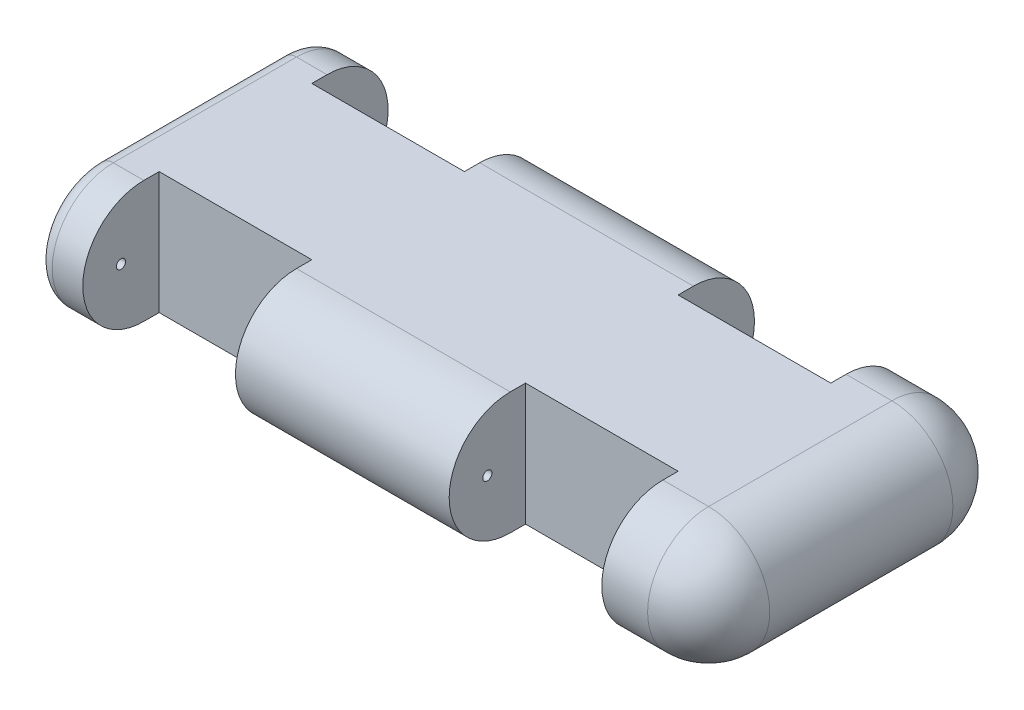
SolidWorks part; units mm, degrees
ref_plane "Front Plane" through (0, 0, 0) normal (0, 0, 1) x (1, 0, 0)
ref_plane "Top Plane" through (0, 0, 0) normal (0, 1, 0) x (1, 0, 0)
ref_plane "Right Plane" through (0, 0, 0) normal (1, 0, 0) x (0, 0, -1)
sketch "Sketch1" plane through (0, 0, 0) normal (0, 1, 0) x (1, 0, 0)
  line L0 (-70, -50) -> (70, -50) construction
  line L1 (-200, 100) -> (-170, 100)
  line L2 (-200, 100) -> (-200, -100)
  line L3 (-200, -100) -> (-170, -100)
  line L4 (200, 100) -> (200, -100)
  line L6 (-170, 100) -> (-170, 50)
  line L7 (-170, 50) -> (-70, 50)
  line L8 (-70, 100) -> (-70, 50)
  line L10 (70, 100) -> (70, 50)
  line L11 (70, 50) -> (170, 50)
  line L12 (170, 100) -> (170, 50)
  line L14 (-170, -100) -> (-170, -50)
  line L15 (-170, -50) -> (-70, -50)
  line L16 (-70, -100) -> (-70, -50)
  line L18 (70, -100) -> (70, -50)
  line L19 (70, -50) -> (170, -50)
  line L20 (170, -100) -> (170, -50)
  line L21 (-70, 50) -> (70, 50) construction
  line L22 (-170, -50) -> (-170, 50) construction
  line L23 (-70, 100) -> (70, 100)
  line L24 (170, 100) -> (200, 100)
  line L25 (170, -100) -> (200, -100)
  line L26 (-70, -100) -> (70, -100)
  point P20 (0, -50)
  point P23 (200, 0)
  point P24 (-170, 0)
  dimension "D1" = 100
  dimension "D2" = 30
  dimension "D3" = 400
  dimension "D4" = 100
  dimension "D5" = 50
extrude "Boss-Extrude1" add sketch "Sketch1" along normal mid plane 80
sketch "Sketch2" plane through (-70, 0, 0) normal (-1, 0, 0) x (0, 0, 1)
  line L0 (-100, 40) -> (-100, -40) construction
  circle A0 centre (-75, 0) radius 3
  dimension "D2" = 6
  dimension "D1" = 25
extrude "Cut-Extrude1" cut sketch "Sketch2" against normal through all both and the other way through all
sketch "Sketch3" plane through (-70, 0, 0) normal (-1, 0, 0) x (0, 0, 1)
  line L0 (100, 40) -> (100, -40) construction
  circle A0 centre (75, 0) radius 3
  dimension "D1" = 6
  dimension "D2" = 25
extrude "Cut-Extrude2" cut sketch "Sketch3" against normal through all both and the other way through all
sketch "Sketch4" plane through (-200, 0, 0) normal (-1, 0, 0) x (0, 0, 1)
  line L0 (-100, 40) -> (-100, -40) construction
  line L1 (-60, -40) -> (-60, -70.29)
  line L2 (-136.8642, 63.9422) -> (-60, 63.9422)
  line L3 (-136.8642, 63.9422) -> (-136.8642, -70.29)
  line L4 (-136.8642, -70.29) -> (-60, -70.29)
  line L5 (-60, 63.9422) -> (-60, 40)
  arc A0 (-60, 40) -> (-60, -40) centre (-60, 0) ccw
  dimension "D1" = 80
extrude "Cut-Extrude3" cut sketch "Sketch4" against normal through all both
sketch "Sketch5" plane through (-200, 0, 0) normal (-1, 0, 0) x (0, 0, 1)
  line L0 (100, 40) -> (100, -40) construction
  line L1 (60, -40) -> (60, -76.3281)
  line L2 (60, 68.8966) -> (141.0543, 68.8966)
  line L3 (60, 68.8966) -> (60, 40)
  line L4 (60, -76.3281) -> (141.0543, -76.3281)
  line L5 (141.0543, 68.8966) -> (141.0543, -76.3281)
  arc A0 (60, -40) -> (60, 40) centre (60, 0) ccw
  dimension "D1" = 80
extrude "Cut-Extrude4" cut sketch "Sketch5" against normal through all both
sketch "Sketch7" plane through (0, 0, 0) normal (0, 0, 1) x (1, 0, 0)
  line L0 (200, 40) -> (170, 40) construction
  line L1 (200, -40) -> (170, -40) construction
  line L2 (200, -3) -> (200, 3) construction
  line L3 (200, 40) -> (200, -40)
  arc A0 (200, -40) -> (200, 40) centre (200, 0) ccw
extrude "Boss-Extrude3" add sketch "Sketch7" along normal mid plane 120
sketch "Sketch8" plane through (0, 0, 60) normal (0, 0, 1) x (1, 0, 0)
  line L0 (200, 40) -> (200, -40)
  arc A0 (200, -40) -> (200, 40) centre (200, 0) ccw
  arc A1 (200, -40) -> (200, 40) centre (200, 0) ccw construction
revolve "Revolve1" add sketch "Sketch8" angle 90 about L0
mirror "Mirror1" about plane through (0, 0, 0) normal (0, 0, 1) of "Revolve1"
fillet "Fillet1" radius 10 4 edges at (-200, 0, -100) (-200, -40, 0) (-200, 0, 100) (-200, 40, 0)
